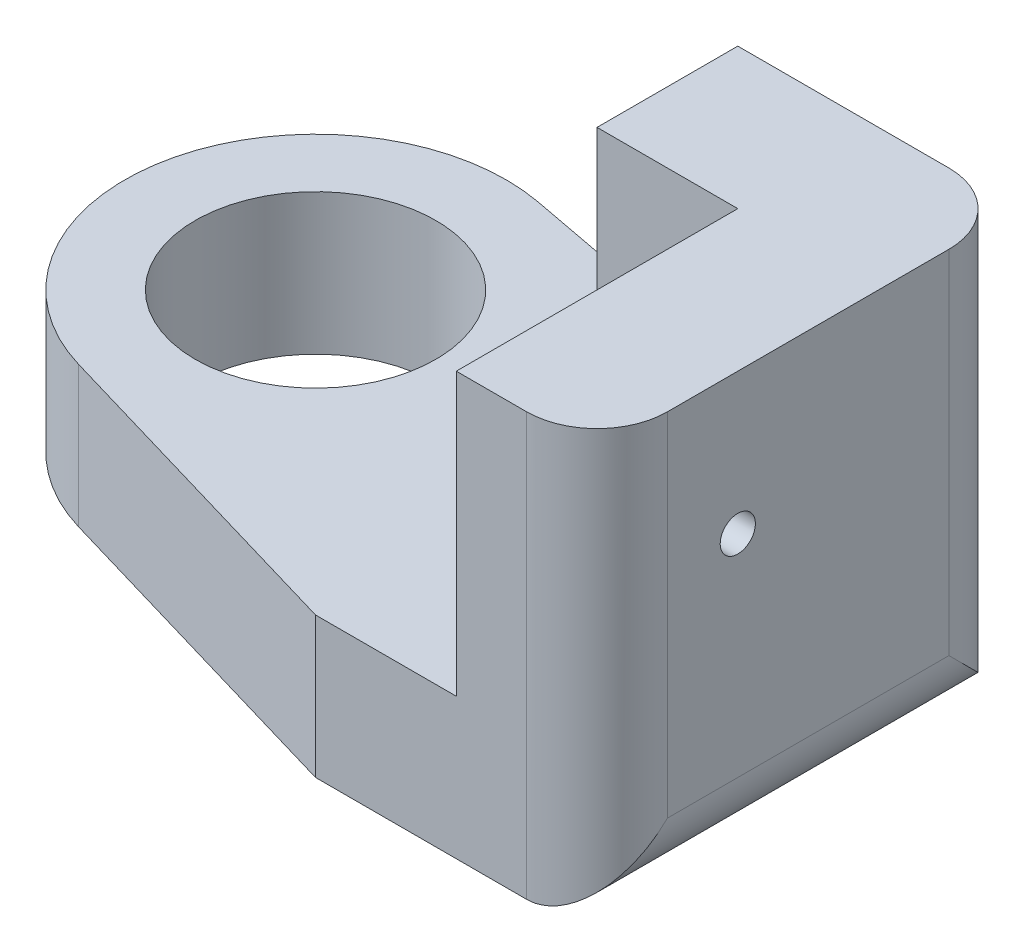
SolidWorks part; units mm, degrees
material "PVC 0.007 Plasticized"
ref_plane "Front Plane" through (0, 0, 0) normal (0, 0, 1) x (1, 0, 0)
ref_plane "Top Plane" through (0, 0, 0) normal (0, 1, 0) x (1, 0, 0)
ref_plane "Right Plane" through (0, 0, 0) normal (1, 0, 0) x (0, 0, -1)
sketch "Sketch1" plane through (0, 0, 0) normal (0, 1, 0) x (1, 0, 0)
  line L1 (0, 0) -> (20, 0)
  line L2 (0, 0) -> (0, -30)
  line L3 (0, -30) -> (20, -30)
  line L4 (20, 0) -> (20, -30)
  dimension "D1" = 30
  dimension "D2" = 20
extrude "Boss-Extrude1" add sketch "Sketch1" along normal blind 10
sketch "Sketch2" plane through (0, 10, 0) normal (0, 1, 0) x (1, 0, 0)
  line L4 (0, 0) -> (0, -10)
  line L5 (0, -10) -> (10, -10)
  line L6 (10, -10) -> (10, -30)
  line L7 (0, -30) -> (20, -30) construction
  line L8 (10, -30) -> (20, -30)
  line L9 (20, -30) -> (20, 0) construction
  line L10 (20, -30) -> (20, 0)
  line L11 (20, 0) -> (0, 0)
  dimension "D1" = 10
  dimension "D2" = 10
extrude "Boss-Extrude2" add sketch "Sketch2" along normal blind 10
sketch "Sketch4" plane through (0, 10, 0) normal (0, 1, 0) x (1, 0, 0)
  line L0 (0, 0) -> (-17.5137, 3.3199)
  line L1 (0, -30) -> (-23.8464, -22.9926)
  line L2 (0, 0) -> (0, -30)
  line L3 (0, 0) -> (0, -30) construction
  line L6 (0, -10) -> (-35.9625, -10) construction
  circle A0 centre (-20, -10) radius 8.55
  arc A1 (-17.5137, 3.3199) -> (-23.8464, -22.9926) centre (-20, -10) ccw
  circle A2 centre (-20, -10) radius 13.55 construction
  dimension "D1" = 17.1
  dimension "D3" = 20
  dimension "D2" = 5
extrude "Boss-Extrude3" add sketch "Sketch4" against normal up to surface (10 mm away) up to face at (10, 0, 15)
fillet "Fillet1" radius 5 4 edges at (0, 10, 5) (20, 0, 15) (20, 10, 30) (20, 10, 0)
sketch "Sketch5" plane through (0, 20, 0) normal (0, 1, 0) x (1, 0, 0)
  line L12 (10, -30) -> (15, -30)
  line L13 (20, -25) -> (20, -5)
  line L14 (15, 0) -> (0, 0)
  line L15 (0, 0) -> (0, -10)
  line L16 (0, -10) -> (10, -10)
  line L17 (10, -10) -> (10, -30)
  line L18 (10, -30) -> (15, -30)
  line L19 (20, -25) -> (20, -5)
  line L20 (15, 0) -> (0, 0)
  line L21 (0, 0) -> (0, -10)
  line L22 (0, -10) -> (10, -10)
  line L23 (10, -10) -> (10, -30)
  arc A4 (15, -30) -> (20, -25) centre (15, -25) ccw
  arc A5 (20, -5) -> (15, 0) centre (15, -5) ccw
  arc A6 (15, -30) -> (20, -25) centre (15, -25) ccw
  arc A7 (20, -5) -> (15, 0) centre (15, -5) ccw
  dimension "D1" = 0
extrude "Boss-Extrude4" add sketch "Sketch5" along normal blind 10
sketch "Sketch6" plane through (10, 0, 0) normal (-1, 0, 0) x (0, 0, 1)
  line L0 (30, 30) -> (30, 10) construction
  line L1 (10, 30) -> (30, 30) construction
  circle A0 centre (20, 20) radius 1.25
  point P5 (30, 20)
  point P8 (20, 30)
  dimension "D1" = 2.5
extrude "Cut-Extrude1" cut sketch "Sketch6" against normal up to surface (10 mm away) up to face at (20, 17.5, 15)
